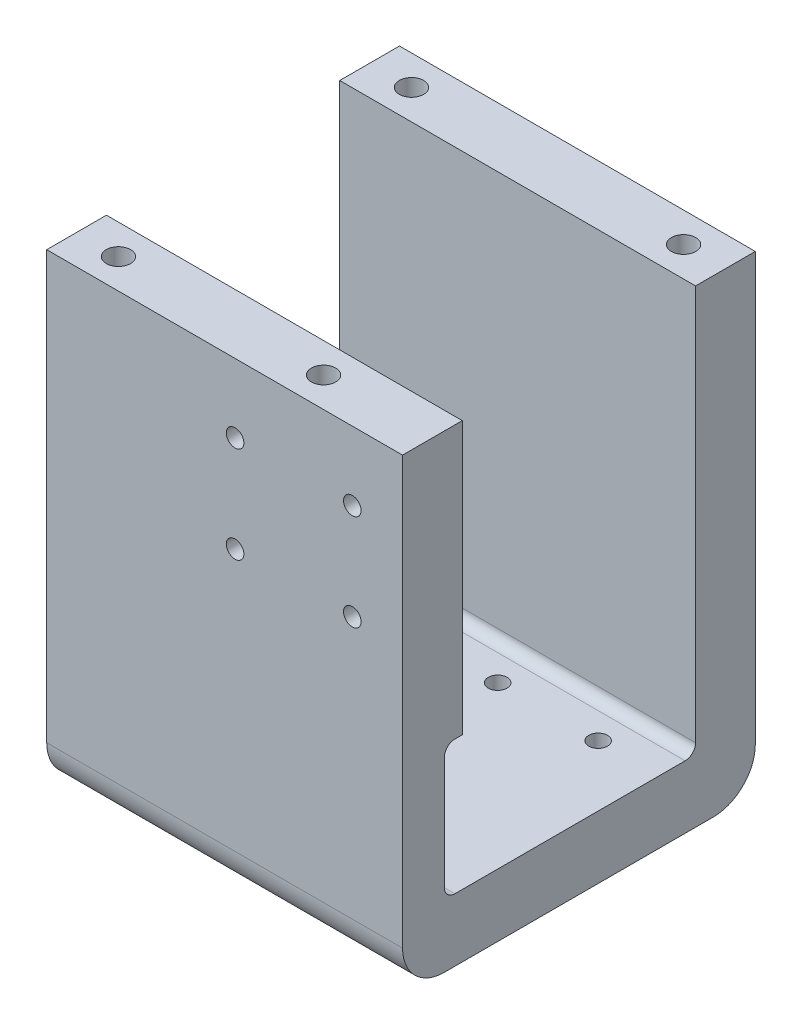
SolidWorks part; units mm, degrees
material "Nylon PA 12"
ref_plane "Front Plane" through (0, 0, 0) normal (0, 0, 1) x (1, 0, 0)
ref_plane "Top Plane" through (0, 0, 0) normal (0, 1, 0) x (1, 0, 0)
ref_plane "Right Plane" through (0, 0, 0) normal (1, 0, 0) x (0, 0, -1)
sketch "Sketch1" plane through (0, 0, 0) normal (0, 1, 0) x (1, 0, 0)
  line L1 (-42.5, -30) -> (42.5, -30)
  line L2 (-42.5, -30) -> (-42.5, 30)
  line L3 (-42.5, 30) -> (42.5, 30)
  line L4 (42.5, -30) -> (42.5, 30)
  line L5 (-42.5, -30) -> (42.5, 30) construction
  line L6 (-42.5, 30) -> (42.5, -30) construction
  point P0 (0, 0)
  dimension "D1" = 60
  dimension "D2" = 85
extrude "Boss-Extrude1" add sketch "Sketch1" along normal mid plane 15
sketch "Sketch2" plane through (0, 7.5, 0) normal (0, 1, 0) x (1, 0, 0)
  line L0 (-42.5, 30) -> (-42.5, -30) construction
  line L1 (-42.5, -30) -> (42.5, -30) construction
  line L2 (3.95, 21.27) -> (3.95, -20.73) construction
  circle A0 centre (3.95, -20.73) radius 2.25
  circle A1 centre (3.95, 21.27) radius 2.25
  circle A2 centre (27.95, 21.27) radius 2.25
  circle A3 centre (27.95, -20.73) radius 2.25
  dimension "D2" = 4.5
  dimension "D4" = 4.5
  dimension "D8" = 4.5
  dimension "D9" = 4.5
  dimension "D1" = 46.45
  dimension "D3" = 9.27
  dimension "D5" = 42
  dimension "D6" = 70.45
  dimension "D10" = 42
extrude "Cut-Extrude1" cut sketch "Sketch2" against normal through all
sketch "Sketch3" plane through (0, 0, 30) normal (0, 0, 1) x (1, 0, 0)
  line L2 (42.5, 104.5) -> (-42.5, 104.5)
  line L4 (-42.5, 104.5) -> (-42.5, -7.5)
  line L5 (-42.5, -7.5) -> (42.5, -7.5)
  line L6 (42.5, 104.5) -> (42.5, -7.5)
  dimension "D1" = 112
extrude "Boss-Extrude2" add sketch "Sketch3" along normal blind 10
fillet "Fillet1" radius 10 1 edges at (0, -7.5, 40)
sketch "Sketch4" plane through (0, 0, 30) normal (0, 0, -1) x (-1, 0, 0)
  line L0 (42.5, 104.5) -> (42.5, 7.5) construction
  line L1 (42.5, 39.5) -> (-42.5, 39.5)
  line L2 (42.5, 39.5) -> (42.5, 104.5)
  line L3 (42.5, 104.5) -> (-42.5, 104.5)
  line L4 (-42.5, 39.5) -> (-42.5, 104.5)
  dimension "D1" = 65
extrude "Boss-Extrude3" add sketch "Sketch4" along normal blind 4.27
sketch "Sketch5" plane through (0, 0, -30) normal (0, 0, -1) x (-1, 0, 0)
  line L1 (-42.5, 104.5) -> (42.5, 104.5)
  line L2 (-42.5, 104.5) -> (-42.5, -7.5)
  line L3 (-42.5, -7.5) -> (42.5, -7.5)
  line L4 (42.5, 104.5) -> (42.5, -7.5)
extrude "Boss-Extrude4" add sketch "Sketch5" along normal blind 14.27
fillet "Fillet2" radius 10 1 edges at (0, -7.5, -44.27)
fillet "Fillet3" radius 2.5 1 edges at (0, 7.5, -30)
fillet "Fillet4" radius 2.5 1 edges at (0, 7.5, 30)
fillet "Fillet5" radius 2.5 1 edges at (0, 39.5, 30)
sketch "Sketch6" plane through (-42.5, 0, 0) normal (-1, 0, 0) x (0, 0, 1)
  line L0 (-30, 10) -> (-30, 104.5) construction
  line L1 (40, 104.5) -> (40, 2.5) construction
  line L4 (-27.5, 7.5) -> (27.5, 7.5) construction
  line L6 (-44.27, 104.5) -> (-30, 104.5) construction
  line L7 (40, 104.5) -> (25.73, 104.5) construction
  circle A0 centre (-37.135, 58.5) radius 2.9
  circle A1 centre (32.865, 58.5) radius 2.9
  circle A3 centre (-2.135, 0) radius 2.9
  dimension "D4" = 5.8
  dimension "D6" = 5.8
  dimension "D8" = 42.135
  dimension "D9" = 5.8
  dimension "D1" = 7.135
  dimension "D2" = 7.135
  dimension "D3" = 7.5
  dimension "D5" = 46
  dimension "D7" = 46
sketch "Sketch7" plane through (0, 104.5, 0) normal (0, 1, 0) x (1, 0, 0)
  line L0 (59.8905, -32.865) -> (-46.8653, -32.865) construction
  line L1 (42.5, -40) -> (-42.5, -40) construction
  line L2 (3.45, 61.4722) -> (3.45, -54.4444) construction
  line L3 (53.2502, 37.135) -> (-49.9301, 37.135) construction
  line L4 (-42.5, 30) -> (42.5, 30) construction
  dimension "D1" = 7.135
  dimension "D2" = 7.135
  dimension "D3" = 3.45
sketch "Sketch8" plane through (0, 104.5, 0) normal (0, 1, 0) x (1, 0, 0)
  line L0 (53.2502, 37.135) -> (-49.9301, 37.135) construction
  line L1 (59.8905, -32.865) -> (-46.8653, -32.865) construction
  line L4 (-42.5, -29.965) -> (-42.5, -35.765) construction
  line L10 (42.5, -40) -> (42.5, -25.73) construction
  circle A0 centre (32.5, 37.135) radius 2.9
  circle A2 centre (-32.5, -32.865) radius 2.9
  circle A3 centre (-32.5, 37.135) radius 2.9
  circle A4 centre (16.5, -32.865) radius 2.9
  dimension "D5" = 5.8
  dimension "D6" = 5.8
  dimension "D1" = 65
  dimension "D2" = 70
  dimension "D3" = 10
  dimension "D4" = 26
extrude "Cut-Extrude2" cut sketch "Sketch8" against normal blind 25
sketch "Sketch9" plane through (0, 0, 40) normal (0, 0, 1) x (1, 0, 0)
  line L0 (42.5, 2.5) -> (42.5, 104.5) construction
  line L1 (59.8905, 104.5) -> (-46.8653, 104.5) construction
  circle A0 centre (30.5, 88.06) radius 2.1
  circle A1 centre (30.5, 65.06) radius 2.1
  circle A2 centre (2.5, 65.06) radius 2.1
  circle A3 centre (2.5, 88.06) radius 2.1
  dimension "D2" = 4.2
  dimension "D4" = 12
  dimension "D6" = 28
  dimension "D1" = 12
  dimension "D3" = 16.44
  dimension "D5" = 23
  dimension "D7" = 28
  dimension "D8" = 23
  dimension "D9" = 40
extrude "Cut-Extrude3" cut sketch "Sketch9" against normal up to surface (14.27 mm away) up to face at (0, 72, 25.73)
extrude "Cut-Extrude4" cut sketch "Sketch6" against normal blind 25
